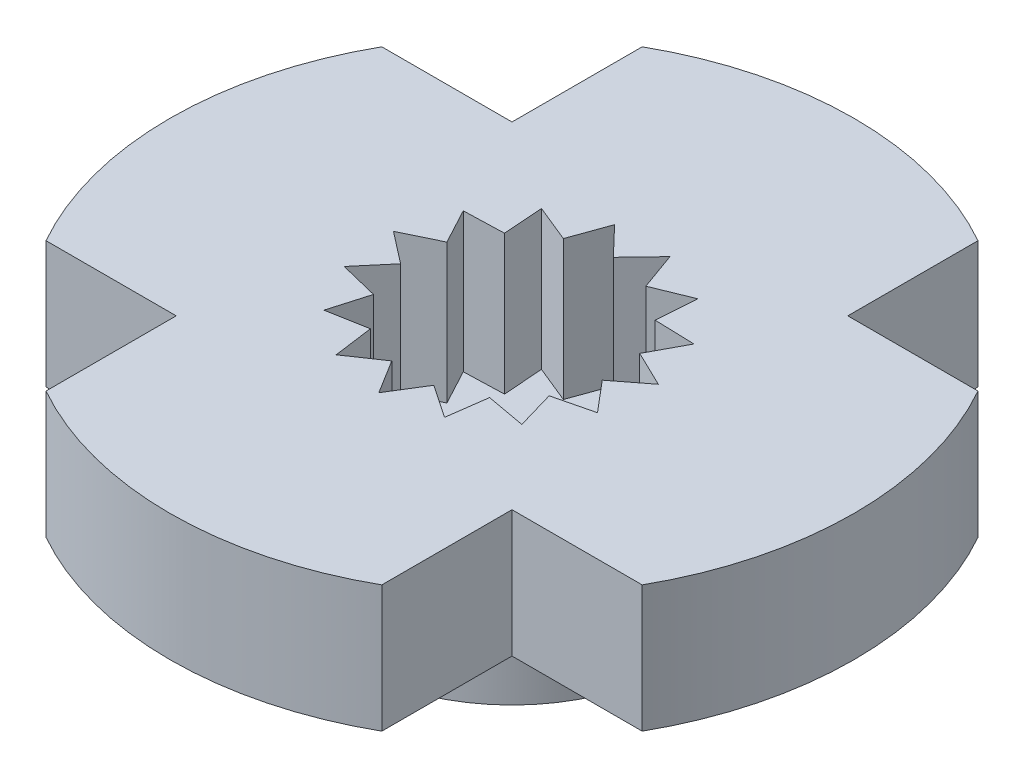
SolidWorks part; units mm, degrees
ref_plane "正面" through (0, 0, 0) normal (0, 0, 1) x (1, 0, 0)
ref_plane "平面" through (0, 0, 0) normal (0, 1, 0) x (1, 0, 0)
ref_plane "右側面" through (0, 0, 0) normal (1, 0, 0) x (0, 0, -1)
sketch "ｽｹｯﾁ1" plane through (0, 0, 0) normal (0, 1, 0) x (1, 0, 0)
  line L30 (0, 1.6) -> (0.437, 2.056) construction
  line L31 (0.6508, 1.4617) -> (1.2355, 1.7005) construction
  line L32 (0.6508, 1.4617) -> (0.437, 2.056) construction
  line L33 (1.189, 1.0706) -> (1.8203, 1.051) construction
  line L34 (1.189, 1.0706) -> (1.2355, 1.7005) construction
  line L35 (1.5217, 0.4944) -> (2.0904, 0.2197) construction
  line L36 (1.5217, 0.4944) -> (1.8203, 1.051) construction
  line L37 (1.5912, -0.1672) -> (1.9991, -0.6495) construction
  line L38 (1.5912, -0.1672) -> (2.0904, 0.2197) construction
  line L39 (1.3856, -0.8) -> (1.562, -1.4065) construction
  line L40 (1.3856, -0.8) -> (1.9991, -0.6495) construction
  line L41 (0.9405, -1.2944) -> (0.8549, -1.9202) construction
  line L42 (0.9405, -1.2944) -> (1.562, -1.4065) construction
  line L43 (0.3327, -1.565) -> (0, -2.1019) construction
  line L44 (0.3327, -1.565) -> (0.8549, -1.9202) construction
  line L45 (-0.3327, -1.565) -> (-0.8549, -1.9202) construction
  line L46 (-0.3327, -1.565) -> (0, -2.1019) construction
  line L47 (-0.9405, -1.2944) -> (-1.562, -1.4065) construction
  line L48 (-0.9405, -1.2944) -> (-0.8549, -1.9202) construction
  line L49 (-1.3856, -0.8) -> (-1.9991, -0.6495) construction
  line L50 (-1.3856, -0.8) -> (-1.562, -1.4065) construction
  line L51 (-1.5912, -0.1672) -> (-2.0904, 0.2197) construction
  line L52 (-1.5912, -0.1672) -> (-1.9991, -0.6495) construction
  line L53 (-1.5217, 0.4944) -> (-1.8203, 1.051) construction
  line L54 (-1.5217, 0.4944) -> (-2.0904, 0.2197) construction
  line L55 (-1.189, 1.0706) -> (-1.2355, 1.7005) construction
  line L56 (-1.189, 1.0706) -> (-1.8203, 1.051) construction
  line L57 (-0.6508, 1.4617) -> (-0.437, 2.056) construction
  line L58 (-0.6508, 1.4617) -> (-1.2355, 1.7005) construction
  line L59 (0, 1.6) -> (-0.437, 2.056) construction
  line L60 (2.65, 4.7051) -> (2.65, 2.65)
  line L61 (-2.65, 4.7051) -> (-2.65, 2.65)
  line L63 (-4.7051, 2.65) -> (-2.65, 2.65)
  line L64 (-4.7051, -2.65) -> (-2.65, -2.65)
  line L65 (-2.65, -2.65) -> (-2.65, -4.7051)
  line L66 (2.65, -2.65) -> (2.65, -4.7051)
  line L67 (2.65, 2.65) -> (4.7051, 2.65)
  line L68 (2.65, -2.65) -> (4.7051, -2.65)
  arc A2 (-4.7051, 2.65) -> (-4.7051, -2.65) centre (0, 0) ccw
  arc A3 (2.65, 4.7051) -> (-2.65, 4.7051) centre (0, 0) ccw
  arc A4 (4.7051, -2.65) -> (4.7051, 2.65) centre (0, 0) ccw
  arc A5 (-2.65, -4.7051) -> (2.65, -4.7051) centre (0, 0) ccw
extrude "ﾎﾞｽ - 押し出し1" add sketch "ｽｹｯﾁ1" along normal blind 2
sketch "ｽｹｯﾁ2" plane through (0, 0, 0) normal (0, -1, 0) x (1, 0, 0)
  circle A0 centre (0, 0) radius 2.575
  circle A1 centre (0, 0) radius 0.85
  dimension "D1" = 5.15
  dimension "D2" = 1.7
extrude "ﾎﾞｽ - 押し出し2" add sketch "ｽｹｯﾁ2" along normal blind 1.5
sketch "ｽｹｯﾁ3" plane through (0, -1.5, 0) normal (0, -1, 0) x (1, 0, 0)
  circle A0 centre (0, 0) radius 1.55
  dimension "D1" = 3.1
extrude "ｶｯﾄ - 押し出し1" cut sketch "ｽｹｯﾁ3" against normal blind 0.3
sketch "ｽｹｯﾁ4" plane through (0, 2, 0) normal (0, 1, 0) x (1, 0, 0)
  line L0 (0, 0) -> (0, 2.4324) construction
  line L1 (0, 0) -> (0.5057, 2.3792) construction
  line L2 (0, 0) -> (0.9893, 2.2221) construction
  line L3 (0, 0) -> (1.4297, 1.9678) construction
  line L4 (0, 0) -> (1.8076, 1.6276) construction
  line L5 (0, 0) -> (2.1065, 1.2162) construction
  line L6 (0, 0) -> (2.3133, 0.7516) construction
  line L7 (0, 0) -> (2.419, 0.2543) construction
  line L24 (0, 0) -> (2.419, -0.2543) construction
  line L25 (0, 0) -> (2.3133, -0.7516) construction
  line L26 (0, 0) -> (2.1065, -1.2162) construction
  line L27 (0, 0) -> (1.8076, -1.6276) construction
  line L28 (0, 0) -> (1.4297, -1.9678) construction
  line L29 (0, 0) -> (0.9893, -2.2221) construction
  line L30 (0, 0) -> (0.5057, -2.3792) construction
  line L31 (0, 0) -> (0, -2.4324) construction
  line L32 (0, 0) -> (-0.5057, -2.3792) construction
  line L33 (0, 0) -> (-0.9893, -2.2221) construction
  line L34 (0, 0) -> (-1.4297, -1.9678) construction
  line L35 (0, 0) -> (-1.8076, -1.6276) construction
  line L36 (0, 0) -> (-2.1065, -1.2162) construction
  line L37 (0, 0) -> (-2.3133, -0.7516) construction
  line L38 (0, 0) -> (-2.419, -0.2543) construction
  line L39 (0, 0) -> (-2.419, 0.2543) construction
  line L40 (0, 0) -> (-2.3133, 0.7516) construction
  line L41 (0, 0) -> (-2.1065, 1.2162) construction
  line L42 (0, 0) -> (-1.8076, 1.6276) construction
  line L43 (0, 0) -> (-1.4297, 1.9678) construction
  line L44 (0, 0) -> (-0.9893, 2.2221) construction
  line L45 (0, 0) -> (-0.5057, 2.3792) construction
  line L46 (0, 1.6) -> (0.437, 2.056)
  line L47 (0.6508, 1.4617) -> (1.2355, 1.7005)
  line L48 (0.6508, 1.4617) -> (0.437, 2.056)
  line L49 (1.189, 1.0706) -> (1.8203, 1.051)
  line L50 (1.189, 1.0706) -> (1.2355, 1.7005)
  line L51 (1.5217, 0.4944) -> (2.0904, 0.2197)
  line L52 (1.5217, 0.4944) -> (1.8203, 1.051)
  line L53 (1.5912, -0.1672) -> (1.9991, -0.6495)
  line L54 (1.5912, -0.1672) -> (2.0904, 0.2197)
  line L55 (1.3856, -0.8) -> (1.562, -1.4065)
  line L56 (1.3856, -0.8) -> (1.9991, -0.6495)
  line L57 (0.9405, -1.2944) -> (0.8549, -1.9202)
  line L58 (0.9405, -1.2944) -> (1.562, -1.4065)
  line L59 (0.3327, -1.565) -> (0, -2.1019)
  line L60 (0.3327, -1.565) -> (0.8549, -1.9202)
  line L61 (-0.3327, -1.565) -> (-0.8549, -1.9202)
  line L62 (-0.3327, -1.565) -> (0, -2.1019)
  line L63 (-0.9405, -1.2944) -> (-1.562, -1.4065)
  line L64 (-0.9405, -1.2944) -> (-0.8549, -1.9202)
  line L65 (-1.3856, -0.8) -> (-1.9991, -0.6495)
  line L66 (-1.3856, -0.8) -> (-1.562, -1.4065)
  line L67 (-1.5912, -0.1672) -> (-2.0904, 0.2197)
  line L68 (-1.5912, -0.1672) -> (-1.9991, -0.6495)
  line L69 (-1.5217, 0.4944) -> (-1.8203, 1.051)
  line L70 (-1.5217, 0.4944) -> (-2.0904, 0.2197)
  line L71 (-1.189, 1.0706) -> (-1.2355, 1.7005)
  line L72 (-1.189, 1.0706) -> (-1.8203, 1.051)
  line L73 (-0.6508, 1.4617) -> (-0.437, 2.056)
  line L74 (-0.6508, 1.4617) -> (-1.2355, 1.7005)
  line L75 (0, 1.6) -> (-0.437, 2.056)
  circle A0 centre (0, 0) radius 1.95 construction
  circle A1 centre (0, 0) radius 1.6 construction
  point P50 (0, 0)
  point P73 (0, 0)
  point P81 (0, 0)
  dimension "D2" = 3.9
  dimension "D3" = 3.2
extrude "ｶｯﾄ - 押し出し2" cut sketch "ｽｹｯﾁ4" against normal blind 2.2
